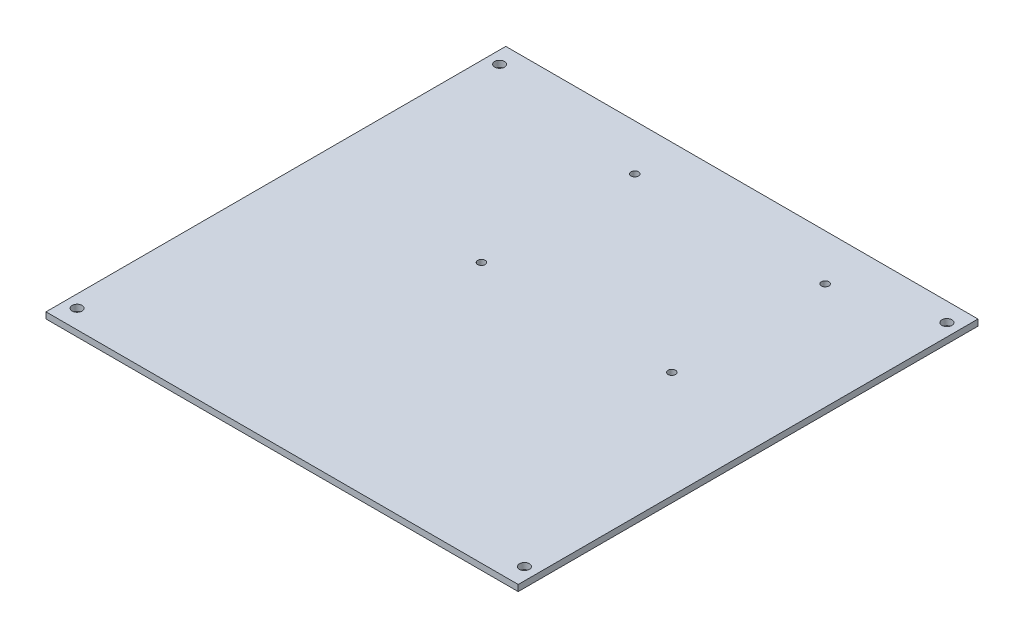
SolidWorks part; units mm, degrees
ref_plane "Front Plane" through (0, 0, 0) normal (0, 0, 1) x (1, 0, 0)
ref_plane "Top Plane" through (0, 0, 0) normal (0, 1, 0) x (1, 0, 0)
ref_plane "Right Plane" through (0, 0, 0) normal (1, 0, 0) x (0, 0, -1)
sketch "Sketch1" plane through (0, 0, 0) normal (0, 1, 0) x (1, 0, 0)
  line L1 (-95, -92.5) -> (95, -92.5)
  line L2 (-95, -92.5) -> (-95, 92.5)
  line L3 (-95, 92.5) -> (95, 92.5)
  line L4 (95, -92.5) -> (95, 92.5)
  line L5 (-95, -92.5) -> (95, 92.5) construction
  line L6 (-95, 92.5) -> (95, -92.5) construction
  point P0 (0, 0)
  dimension "D1" = 190
  dimension "D2" = 185
extrude "Boss-Extrude1" add sketch "Sketch1" along normal blind 2.5
sketch "Sketch2" plane through (0, 2.5, 0) normal (0, 1, 0) x (1, 0, 0)
  text T0 "TOP" font "Century Gothic" height in points 72
extrude "Cut-Extrude1" [suppressed] cut sketch "Sketch2" against normal blind 1
sketch "Sketch3" plane through (0, 2.5, 0) normal (0, 1, 0) x (1, 0, 0)
  line L0 (95, 92.5) -> (-95, 92.5) construction
  line L1 (-95, 92.5) -> (-95, -92.5) construction
  line L2 (-95, -92.5) -> (95, -92.5) construction
  line L3 (0, -1000) -> (0, 49000) construction
  circle A0 centre (-90, 85) radius 2
  circle A1 centre (-90, -85) radius 2
  circle A2 centre (90, 85) radius 2
  circle A3 centre (90, -85) radius 2
  dimension "D1" = 4
  dimension "D2" = 7.5
  dimension "D3" = 5
  dimension "D4" = 4
  dimension "D5" = 5
  dimension "D6" = 7.5
extrude "Cut-Extrude2" cut sketch "Sketch3" against normal blind 10
sketch "Sketch4" plane through (0, 2.5, 0) normal (0, 1, 0) x (1, 0, 0)
  line L0 (95, -92.5) -> (95, 92.5) construction
  line L1 (95, 92.5) -> (-95, 92.5) construction
  circle A0 centre (52, 74) radius 1.5
  circle A1 centre (-24.6, 74) radius 1.5
  circle A2 centre (-24.6, 12.3) radius 1.5
  circle A3 centre (52, 12.3) radius 1.5
  dimension "D1" = 3
  dimension "D2" = 43
  dimension "D3" = 18.5
  dimension "D4" = 2
  dimension "D5" = 2
extrude "Cut-Extrude3" cut sketch "Sketch4" against normal blind 10
